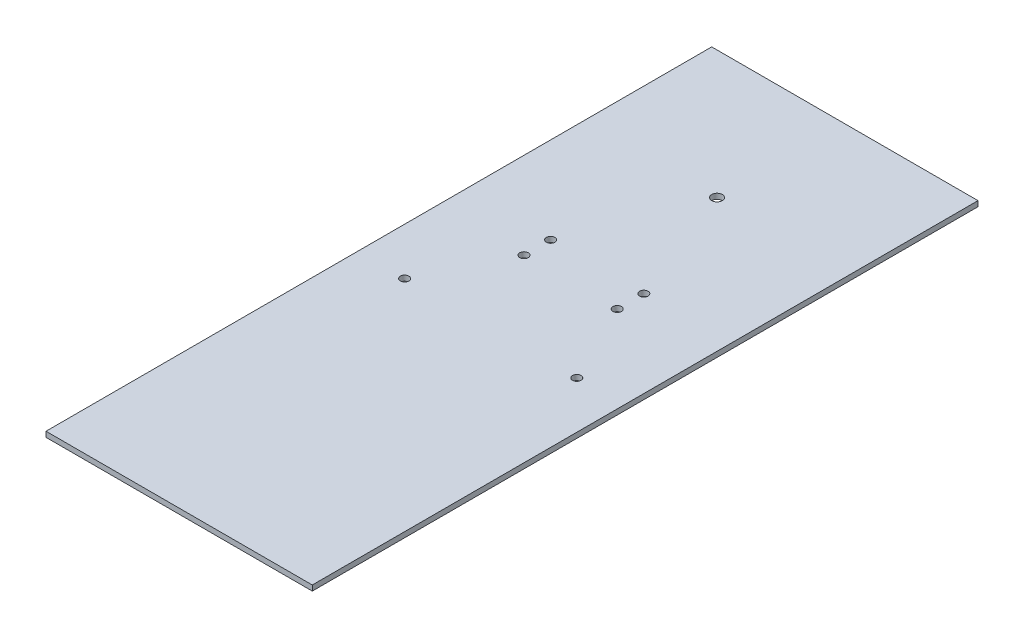
SolidWorks part; units mm, degrees
ref_plane "前视基准面" through (0, 0, 0) normal (0, 0, 1) x (1, 0, 0)
ref_plane "上视基准面" through (0, 0, 0) normal (0, 1, 0) x (1, 0, 0)
ref_plane "右视基准面" through (0, 0, 0) normal (1, 0, 0) x (0, 0, -1)
sketch "草图1" plane through (0, 0, 0) normal (0, 1, 0) x (1, 0, 0)
  line L1 (-50, -200) -> (50, -200)
  line L2 (-50, -200) -> (-50, 200)
  line L3 (-50, 200) -> (50, 200)
  line L4 (50, -200) -> (50, 200)
  line L5 (-50, -200) -> (50, 200) construction
  line L6 (-50, 200) -> (50, -200) construction
  point P0 (0, 0)
  dimension "D1" = 400
  dimension "D2" = 100
extrude "凸台-拉伸1" add sketch "草图1" along normal blind 2
sketch "草图3" plane through (0, 0, 0) normal (0, -1, 0) x (1, 0, 0)
  line L0 (0, 0) -> (0, -106.9989) construction
  circle A0 centre (0, -152) radius 2
  dimension "D1" = 4
  dimension "D2" = 152
extrude "切除-拉伸2" cut sketch "草图3" against normal up to next
sketch "草图4" plane through (0, 0, 0) normal (0, -1, 0) x (1, 0, 0)
  circle A0 centre (17.5, -97) radius 1.6 construction
  circle A1 centre (17.5, -107) radius 1.6 construction
  circle A2 centre (32.3205, -67) radius 1.6 construction
  circle A3 centre (-17.5, -97) radius 1.6 construction
  circle A4 centre (-17.5, -107) radius 1.6 construction
  circle A5 centre (-32.3205, -67) radius 1.6 construction
  circle A6 centre (17.5, -97) radius 1.6
  circle A7 centre (17.5, -107) radius 1.6
  circle A8 centre (32.3205, -67) radius 1.6
  circle A9 centre (-17.5, -97) radius 1.6
  circle A10 centre (-17.5, -107) radius 1.6
  circle A11 centre (-32.3205, -67) radius 1.6
extrude "切除-拉伸3" cut sketch "草图4" against normal up to next
sketch "草图5" plane through (0, 0, 0) normal (0, -1, 0) x (1, 0, 0)
  line L0 (50, 200) -> (50, -200) construction
  line L1 (-50, 200) -> (50, 200)
  line L2 (-50, 200) -> (-50, 50)
  line L3 (-50, 50) -> (50, 50)
  line L4 (50, 200) -> (50, 50)
  dimension "D1" = 150
extrude "切除-拉伸4" cut sketch "草图5" against normal up to next
